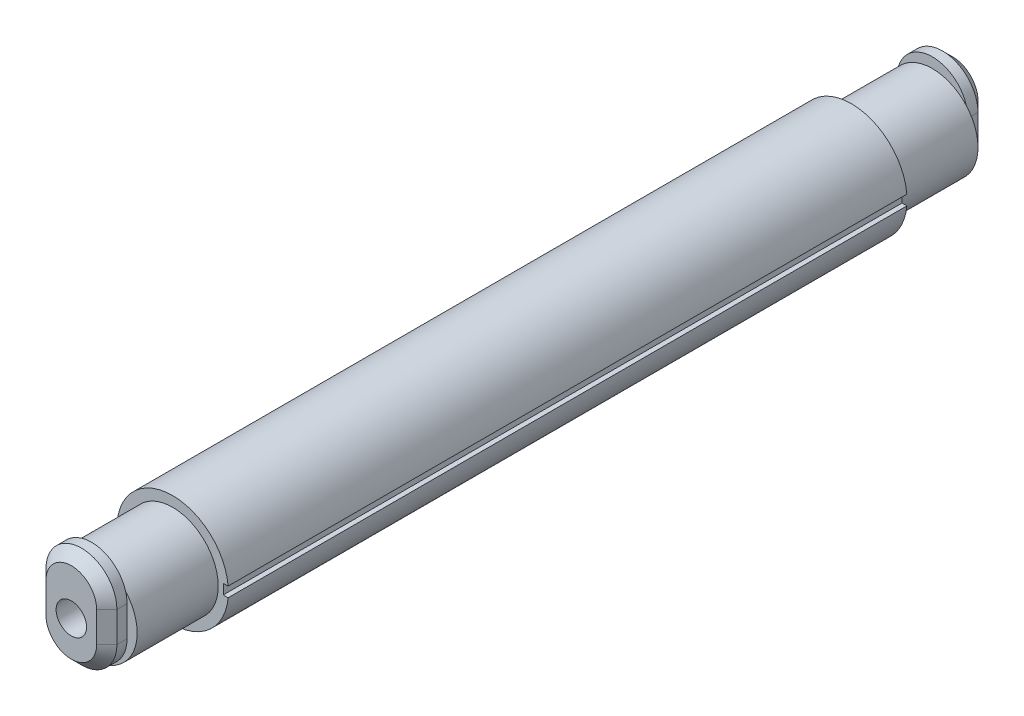
SolidWorks part; units mm, degrees
material "PET"
ref_plane "Front Plane" through (0, 0, 0) normal (0, 0, 1) x (1, 0, 0)
ref_plane "Top Plane" through (0, 0, 0) normal (0, 1, 0) x (1, 0, 0)
ref_plane "Right Plane" through (0, 0, 0) normal (1, 0, 0) x (0, 0, -1)
sketch "Sketch1" plane through (0, 0, 0) normal (0, 0, 1) x (1, 0, 0)
  circle A0 centre (0, 0) radius 5.5
extrude "Boss-Extrude1" add sketch "Sketch1" along normal blind 67
sketch "Sketch2" plane through (0, 0, 0) normal (0, 0, -1) x (-1, 0, 0)
  line L1 (5, 0.5) -> (6, 0.5)
  line L2 (5, 0.5) -> (5, -0.5)
  line L3 (5, -0.5) -> (6, -0.5)
  line L4 (6, 0.5) -> (6, -0.5)
  line L5 (5, 0.5) -> (6, -0.5) construction
  line L6 (5, -0.5) -> (6, 0.5) construction
  line L7 (-6, 0.5) -> (-5, 0.5)
  line L8 (-6, 0.5) -> (-6, -0.5)
  line L9 (-6, -0.5) -> (-5, -0.5)
  line L10 (-5, 0.5) -> (-5, -0.5)
  line L11 (-6, 0.5) -> (-5, -0.5) construction
  line L12 (-6, -0.5) -> (-5, 0.5) construction
  circle A0 centre (0, 0) radius 5.5 construction
  point P0 (5.5, 0)
  point P7 (-5.5, 0)
  dimension "D1" = 1
  dimension "D2" = 1
  dimension "D3" = 1
extrude "Cut-Extrude1" cut sketch "Sketch2" against normal blind 67
sketch "Sketch3" plane through (0, 0, 67) normal (0, 0, 1) x (1, 0, 0)
  circle A0 centre (0, 0) radius 4.5
extrude "Boss-Extrude2" add sketch "Sketch3" along normal blind 8
sketch "Sketch4" plane through (0, 0, 75) normal (0, 0, 1) x (1, 0, 0)
  line L0 (0, -0.9928) -> (0, 2.0072) construction
  line L3 (-3.5, -0.9928) -> (-3.5, 2.0072)
  line L4 (3.5, -0.9928) -> (3.5, 2.0072)
  arc A2 (-3.5, -0.9928) -> (3.5, -0.9928) centre (0, -0.9928) ccw
  arc A3 (3.5, 2.0072) -> (-3.5, 2.0072) centre (0, 2.0072) ccw
  point P3 (0, 0.5072)
  point P14 (0, 5.5072)
  point P15 (0, -4.4928)
  dimension "D1" = 7
  dimension "D2" = 10
extrude "Boss-Extrude3" add sketch "Sketch4" along normal blind 2
chamfer "Chamfer1" distance 1 angle 45 4 edges at (3.5, 0.5072, 77) (0, 5.5072, 77) (0, -4.4928, 77) (-3.5, 0.5072, 77)
ref_plane "Plane1" through (0, 0, 33.5) normal (0, 0, 1) x (1, 0, 0)
mirror "Mirror1" about plane through (0, 0, 33.5) normal (0, 0, 1) of "Boss-Extrude2", "Boss-Extrude3", "Chamfer1"
sketch "Sketch7" plane through (0, 0, -10) normal (0, 0, -1) x (-1, 0, 0)
  circle A0 centre (0, 0) radius 1.5
hole_wizard "Ø3.0mm Dowel Hole1" positions "Sketch9" profile "Sketch10" hole size "Ø3.0" standard "KS" end condition through all
sketch "Sketch9" plane through (0, 0, -10) normal (0, 0, -1) x (-1, 0, 0)
  point P0 (0, 0)
sketch "Sketch10" plane through (0, 0, -10) normal (1, 0, 0) x (0, 1, 0)
  line L0 (0, 0) -> (0, 87)
  line L1 (0, 87) -> (1.5, 87)
  line L2 (1.5, 87) -> (1.5, 0.0241)
  line L3 (1.5, 0.0241) -> (1.525, 0)
  line L5 (1.525, 0) -> (0, 0)
  line L6 (-1.5, 0.0241) -> (-1.525, 0) construction
  line L11 (0, -6.35) -> (0, 107.95) construction
  dimension "Thru Hole Dia." = 3
  dimension "Thru Hole Depth" = 87
  dimension "Near C'Sink Dia." = 3.05
  dimension "Near C'Sink Angle" = 92
